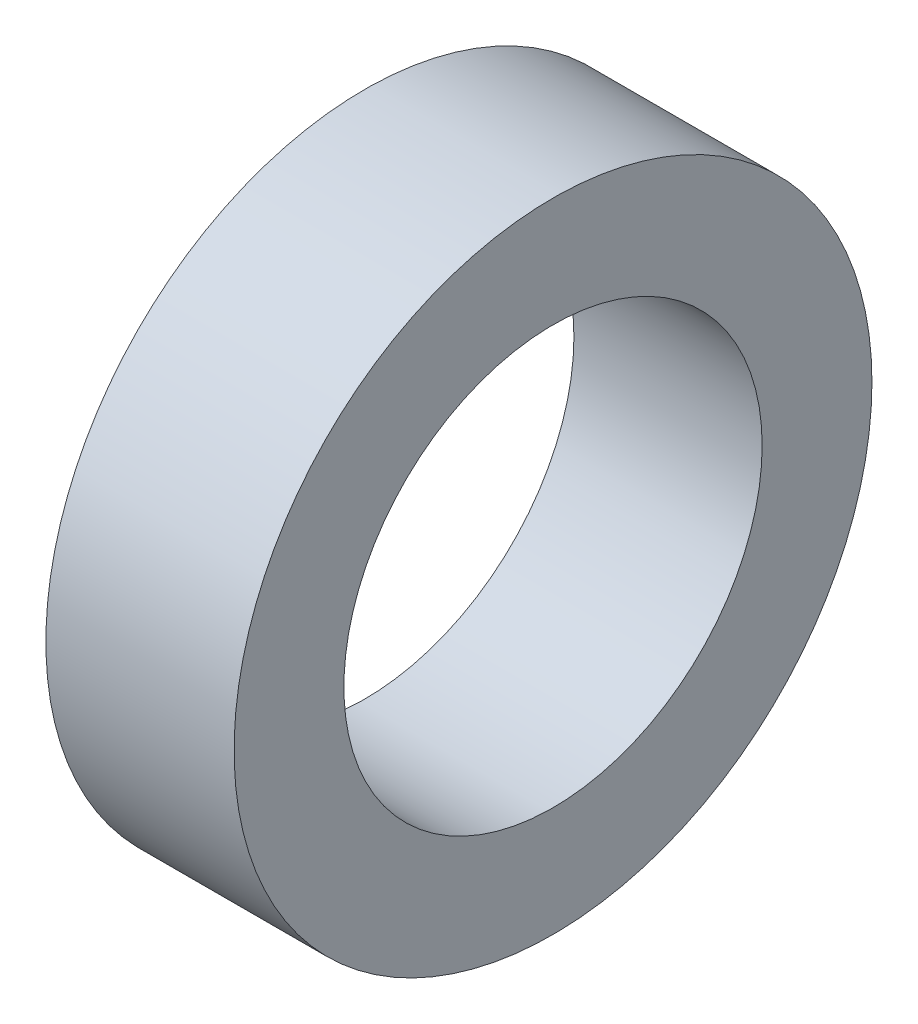
SolidWorks part; units mm, degrees
ref_plane "Front Plane" through (0, 0, 0) normal (0, 0, 1) x (1, 0, 0)
ref_plane "Top Plane" through (0, 0, 0) normal (0, 1, 0) x (1, 0, 0)
ref_plane "Right Plane" through (0, 0, 0) normal (1, 0, 0) x (0, 0, -1)
sketch "Sketch1" plane through (0, 0, 0) normal (1, 0, 0) x (0, 0, -1)
  line L5 (-1.5, -1.5) -> (1.5, 1.5) construction
  line L6 (-1.5, 1.5) -> (1.5, -1.5) construction
  circle A0 centre (0, 0) radius 6.1
  circle A1 centre (0, 0) radius 4
  dimension "D1" = 12.2
extrude "Boss-Extrude1" add sketch "Sketch1" along normal blind 3.6
